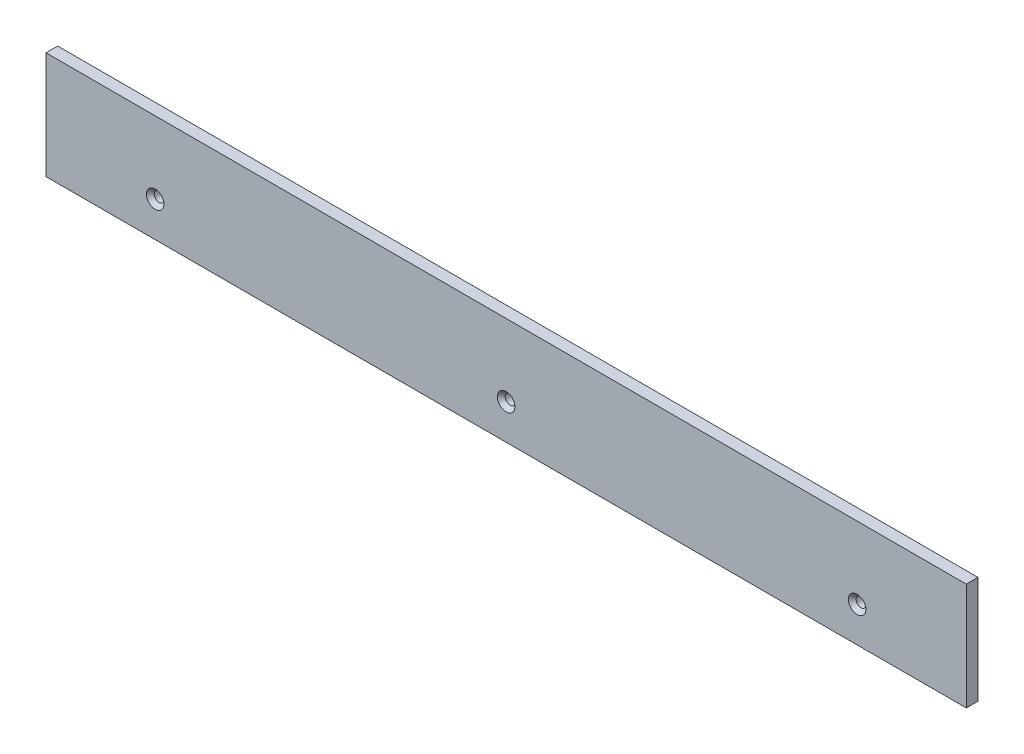
SolidWorks part; units mm, degrees
ref_plane "Plan de face" through (0, 0, 0) normal (0, 0, 1) x (1, 0, 0)
ref_plane "Plan de dessus" through (0, 0, 0) normal (0, 1, 0) x (1, 0, 0)
ref_plane "Plan de droite" through (0, 0, 0) normal (1, 0, 0) x (0, 0, -1)
sketch "Esquisse1" plane through (0, 0, 0) normal (0, 0, 1) x (1, 0, 0)
  line L1 (-236, -27.5) -> (236, -27.5)
  line L2 (-236, -27.5) -> (-236, 27.5)
  line L3 (-236, 27.5) -> (236, 27.5)
  line L4 (236, -27.5) -> (236, 27.5)
  line L5 (-236, -27.5) -> (236, 27.5) construction
  line L6 (-236, 27.5) -> (236, -27.5) construction
  point P0 (0, 0)
  dimension "D1" = 55
  dimension "D2" = 472
extrude "Boss.-Extru.1" add sketch "Esquisse1" along normal blind 6
sketch "Esquisse5" plane through (0, 0, 6) normal (0, 0, 1) x (1, 0, 0)
  line L0 (-180, -9.5) -> (180, -9.5) construction
  line L2 (-236, -27.5) -> (236, -27.5) construction
  point P0 (-180, -9.5)
  point P2 (0, -9.5)
  point P4 (180, -9.5)
  point P12 (-5.3489, -18.1225)
  point P13 (0, 0)
  dimension "D1" = 360
  dimension "D2" = 18
hole_wizard "Fraisage pour Vis tête conique M51" positions "Esquisse5" profile "Esquisse4" countersink size "M5" standard "ISO"
sketch "Esquisse4" plane through (-180, -9.5, 6) normal (1, 0, 0) x (0, -1, 0)
  line L0 (0, 0) -> (0, 6)
  line L1 (0, 6) -> (2.75, 6)
  line L2 (2.75, 6) -> (2.75, 2.45)
  line L3 (2.75, 2.45) -> (5.2, 0)
  line L5 (5.2, 0) -> (0, 0)
  line L6 (-2.75, 2.45) -> (-5.2, 0) construction
  line L11 (0, -6.35) -> (0, 107.95) construction
  dimension "Diamètre du perçage jusqu'au prochain" = 5.5
  dimension "Profondeur du perçage jusqu'au prochain" = 6
  dimension "Diamètre du fraisage entrant" = 10.4
  dimension "Angle du fraisage entrant" = 90
sketch "Esquisse6" plane through (0, 0, 6) normal (0, 0, 1) x (1, 0, 0)
  line L0 (-180, -9.5) -> (180, -9.5) construction
  line L1 (-236, -27.5) -> (236, -27.5) construction
  circle A0 centre (-180, -9.5) radius 2.5
  circle A1 centre (0, -9.5) radius 2.5
  circle A2 centre (180, -9.5) radius 2.5
  point P2 (0, -9.5)
  dimension "D1" = 5
  dimension "D2" = 18
  dimension "D3" = 360
extrude "Enlèv. mat.-Extru.1" cut sketch "Esquisse6" against normal through all
chamfer "Chanfrein1" distance 2 angle 45 3 edges at (182.5, -9.5, 6) (2.5, -9.5, 6) (-177.5, -9.5, 6)
